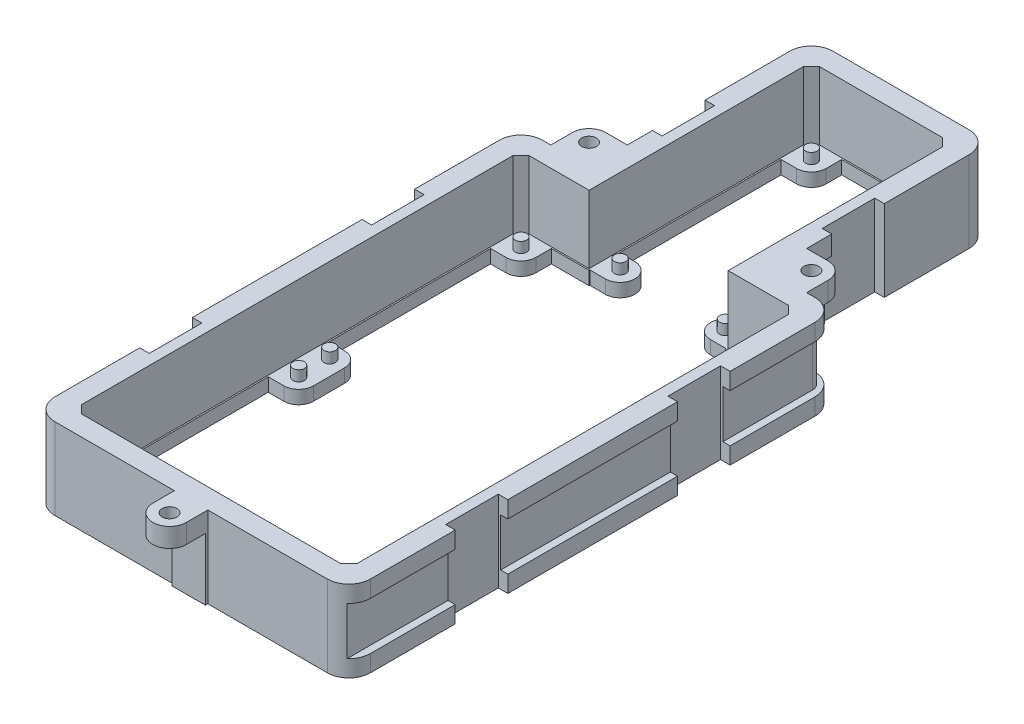
SolidWorks part; units mm, degrees
ref_plane "Front Plane" through (0, 0, 0) normal (0, 0, 1) x (1, 0, 0)
ref_plane "Top Plane" through (0, 0, 0) normal (0, 1, 0) x (1, 0, 0)
ref_plane "Right Plane" through (0, 0, 0) normal (1, 0, 0) x (0, 0, -1)
sketch "Sketch1" plane through (0, 0, 0) normal (0, 1, 0) x (1, 0, 0)
  line L0 (0, 46.5) -> (0, 93) construction
  line L1 (-28.5, 46.5) -> (-14.25, 46.5)
  line L2 (-28.5, 46.5) -> (-28.5, -46.5)
  line L3 (-28.5, -46.5) -> (28.5, -46.5)
  line L4 (28.5, 46.5) -> (28.5, -46.5)
  line L5 (-28.5, 46.5) -> (28.5, -46.5) construction
  line L6 (-28.5, -46.5) -> (28.5, 46.5) construction
  line L7 (14.25, 46.5) -> (28.5, 46.5)
  line L8 (-14.25, 93) -> (14.25, 93)
  line L9 (-14.25, 93) -> (-14.25, 46.5)
  line L11 (14.25, 93) -> (14.25, 46.5)
  line L12 (-14.25, 93) -> (14.25, 46.5) construction
  line L13 (-14.25, 46.5) -> (14.25, 93) construction
  point P0 (0, 0)
  point P8 (0, 69.75)
  dimension "D1" = 93
  dimension "D2" = 57
  dimension "D3" = 28.5
  dimension "D4" = 46.5
extrude "Extrude-Thin1" add sketch "Sketch1" along normal blind 17 thin thin type one direction wall 5
chamfer "Chamfer1" distance 1.5 angle 45 6 edges at (28.5, 8.5, 46.5) (-28.5, 8.5, 46.5) (-14.25, 8.5, -93) (14.25, 8.5, -93) (28.5, 8.5, -46.5) (-28.5, 8.5, -46.5)
sketch "Sketch2" plane through (0, 0, 0) normal (0, 1, 0) x (1, 0, 0)
  line L0 (44.0939, -43.25) -> (-48.3483, -43.25) construction
  line L1 (46.9827, -3.25) -> (-50.6815, -3.25) construction
  line L2 (46.9827, 3.25) -> (-51.7928, 3.25) construction
  line L3 (46.2049, 43.25) -> (-54.3481, 43.25) construction
  line L4 (46.2049, 49.75) -> (-56.7925, 49.75) construction
  line L5 (33.6497, 89.75) -> (-41.3484, 89.75) construction
  line L6 (25.25, -65.6753) -> (25.25, 75.099) construction
  line L7 (-25.25, -68.1197) -> (-25.25, 95.7651) construction
  line L8 (-11, 103.0983) -> (-11, 26.7668) construction
  line L9 (11, 105.5427) -> (11, 26.7668) construction
  line L10 (-27, -46.5) -> (27, -46.5) construction
  line L11 (28.5, -45) -> (28.5, 45) construction
  line L12 (-28.5, 45) -> (-28.5, -45) construction
  line L13 (-14.25, 91.5) -> (-14.25, 46.5) construction
  line L14 (3.25, -77.4697) -> (3.25, -8.4056) construction
  line L15 (14.25, 46.5) -> (14.25, 91.5) construction
  line L16 (27, 46.5) -> (14.25, 46.5) construction
  line L17 (12.75, 93) -> (-12.75, 93) construction
  line L18 (-3.25, -74.7071) -> (-3.25, -10.5676) construction
  circle A0 centre (11, 89.75) radius 1.2
  circle A1 centre (-11, 89.75) radius 1.2
  circle A2 centre (11, 49.75) radius 1.2
  circle A3 centre (-11, 49.75) radius 1.2
  circle A4 centre (25.25, -43.25) radius 1.2
  circle A5 centre (25.25, 43.25) radius 1.2
  circle A6 centre (25.25, 3.25) radius 1.2
  circle A7 centre (25.25, -3.25) radius 1.2
  circle A8 centre (-25.25, -43.25) radius 1.2
  circle A9 centre (-25.25, -3.25) radius 1.2
  circle A10 centre (-25.25, 3.25) radius 1.2
  circle A11 centre (-25.25, 43.25) radius 1.2
  circle A12 centre (3.25, -43.25) radius 1.2
  circle A13 centre (-3.25, -43.25) radius 1.2
  dimension "D11" = 2.4
  dimension "D1" = 3.25
  dimension "D2" = 3.25
  dimension "D3" = 3.25
  dimension "D4" = 40
  dimension "D5" = 6.5
  dimension "D6" = 40
  dimension "D7" = 3.25
  dimension "D8" = 3.25
  dimension "D9" = 3.25
  dimension "D10" = 3.25
  dimension "D12" = 22
  dimension "D13" = 22
extrude "Boss-Extrude1" add sketch "Sketch2" along normal blind 5 separate body
sketch "Sketch3" plane through (0, 0, 0) normal (0, -1, 0) x (-1, 0, 0)
  line L0 (14.25, 53) -> (14.25, 86.5)
  line L1 (7.75, 93) -> (-7.75, 93)
  line L2 (-14.25, 86.5) -> (-14.25, 53)
  line L3 (-14.25, 46.5) -> (-22, 46.5)
  line L4 (-28.5, 40) -> (-28.5, 6.5)
  line L5 (-22, -46.5) -> (-6.5, -46.5)
  line L6 (28.5, -40) -> (28.5, -6.5)
  line L7 (22, 46.5) -> (14.25, 46.5)
  line L8 (22, 43.25) -> (22, 46.5)
  line L9 (25.25, 40) -> (28.5, 40)
  line L10 (25.25, 6.5) -> (28.5, 6.5)
  line L11 (22, 3.25) -> (22, -3.25)
  line L12 (25.25, -6.5) -> (28.5, -6.5)
  line L13 (25.25, -40) -> (28.5, -40)
  line L14 (22, -43.25) -> (22, -46.5)
  line L15 (-25.25, -40) -> (-28.5, -40)
  line L16 (-22, -43.25) -> (-22, -46.5)
  line L17 (-25.25, -6.5) -> (-28.5, -6.5)
  line L18 (-22, -3.25) -> (-22, 3.25)
  line L19 (-25.25, 6.5) -> (-28.5, 6.5)
  line L20 (-25.25, 40) -> (-28.5, 40)
  line L21 (-22, 43.25) -> (-22, 46.5)
  line L22 (-11, 53) -> (-14.25, 53)
  line L23 (-14.25, 46.5) -> (-11, 46.5)
  line L24 (14.25, 46.5) -> (11, 46.5)
  line L25 (11, 53) -> (14.25, 53)
  line L26 (7.75, 89.75) -> (7.75, 93)
  line L27 (11, 86.5) -> (14.25, 86.5)
  line L28 (-11, 86.5) -> (-14.25, 86.5)
  line L29 (-7.75, 89.75) -> (-7.75, 93)
  line L30 (-28.5, -6.5) -> (-28.5, -40)
  line L31 (28.5, 6.5) -> (28.5, 40)
  line L32 (33.5, -51.5) -> (-33.5, -51.5)
  line L33 (-33.5, -51.5) -> (-33.5, 51.5)
  line L34 (-33.5, 51.5) -> (-19.25, 51.5)
  line L35 (-19.25, 51.5) -> (-19.25, 98)
  line L36 (-19.25, 98) -> (19.25, 98)
  line L37 (19.25, 98) -> (19.25, 51.5)
  line L38 (19.25, 51.5) -> (33.5, 51.5)
  line L39 (33.5, 51.5) -> (33.5, -51.5)
  line L40 (-6.5, -43.25) -> (-6.5, -46.5)
  line L41 (-3.25, -40) -> (3.25, -40)
  line L42 (6.5, -43.25) -> (6.5, -46.5)
  line L43 (6.5, -46.5) -> (22, -46.5)
  arc A0 (-11, 46.5) -> (-11, 53) centre (-11, 49.75) ccw
  arc A1 (-11, 86.5) -> (-7.75, 89.75) centre (-11, 89.75) ccw
  arc A2 (7.75, 89.75) -> (11, 86.5) centre (11, 89.75) ccw
  arc A3 (11, 53) -> (11, 46.5) centre (11, 49.75) ccw
  arc A4 (22, 43.25) -> (25.25, 40) centre (25.25, 43.25) ccw
  arc A5 (25.25, 6.5) -> (22, 3.25) centre (25.25, 3.25) ccw
  arc A6 (22, -3.25) -> (25.25, -6.5) centre (25.25, -3.25) ccw
  arc A7 (25.25, -40) -> (22, -43.25) centre (25.25, -43.25) ccw
  arc A8 (-22, -43.25) -> (-25.25, -40) centre (-25.25, -43.25) ccw
  arc A9 (-25.25, -6.5) -> (-22, -3.25) centre (-25.25, -3.25) ccw
  arc A10 (-22, 3.25) -> (-25.25, 6.5) centre (-25.25, 3.25) ccw
  arc A11 (-25.25, 40) -> (-22, 43.25) centre (-25.25, 43.25) ccw
  arc A13 (6.5, -43.25) -> (3.25, -40) centre (3.25, -43.25) ccw
  arc A14 (-3.25, -40) -> (-6.5, -43.25) centre (-3.25, -43.25) ccw
extrude "Boss-Extrude3" add sketch "Sketch3" against normal blind 2.8
sketch "Sketch4" plane through (0, 17, 0) normal (0, 1, 0) x (1, 0, 0)
  line L0 (-19.25, 98) -> (-19.25, 51.5) construction
  line L1 (-19.25, 51.5) -> (-33.5, 51.5) construction
  line L2 (-27.25, 55.5) -> (-27.25, 51.5)
  line L3 (-27.25, 51.5) -> (-19.25, 51.5)
  line L4 (-19.25, 51.5) -> (-19.25, 59.5)
  line L5 (-19.25, 59.5) -> (-23.25, 59.5)
  line L6 (19.25, 51.5) -> (19.25, 98) construction
  line L7 (33.5, 51.5) -> (19.25, 51.5) construction
  line L8 (23.25, 59.5) -> (19.25, 59.5)
  line L9 (19.25, 59.5) -> (19.25, 51.5)
  line L10 (19.25, 51.5) -> (27.25, 51.5)
  line L11 (27.25, 51.5) -> (27.25, 55.5)
  arc A0 (-23.25, 59.5) -> (-27.25, 55.5) centre (-23.25, 55.5) ccw
  circle A1 centre (-23.25, 55.5) radius 1.55
  arc A2 (27.25, 55.5) -> (23.25, 59.5) centre (23.25, 55.5) ccw
  circle A3 centre (23.25, 55.5) radius 1.55
  dimension "D1" = 8
  dimension "D2" = 8
extrude "Boss-Extrude4" add sketch "Sketch4" against normal blind 4
sketch "Sketch5" plane through (0, 17, 0) normal (0, 1, 0) x (1, 0, 0)
  line L0 (-33.5, -51.5) -> (33.5, -51.5) construction
  line L1 (-4, -55.5) -> (-4, -51.5)
  line L2 (-4, -51.5) -> (4, -51.5)
  line L3 (4, -51.5) -> (4, -55.5)
  arc A0 (-4, -55.5) -> (4, -55.5) centre (0, -55.5) ccw
  circle A1 centre (0, -55.5) radius 1.55
  dimension "D1" = 8
  dimension "D2" = 4
extrude "Boss-Extrude5" add sketch "Sketch5" against normal blind 4
fillet "Fillet1" radius 5 6 edges at (-19.25, 8.5, -98) (-33.5, 8.5, -51.5) (-33.5, 8.5, 51.5) (33.5, 8.5, 51.5) (19.25, 8.5, -98) (33.5, 8.5, -51.5)
sketch "Sketch6" plane through (0, 17, 0) normal (0, 1, 0) x (1, 0, 0)
  line L0 (-25.25, 6.5) -> (-25.25, 40) construction
  line L1 (25.25, 40) -> (25.25, 6.5) construction
  line L2 (-25.25, -6.5) -> (-25.25, -40) construction
  line L3 (25.25, -6.5) -> (25.25, -40) construction
  line L4 (0, -23.25) -> (-33.5, -23.25) construction
  line L5 (-33.5, 46.5) -> (-33.5, -46.5) construction
  line L6 (0, -23.25) -> (33.5, -23.25) construction
  line L7 (33.5, -46.5) -> (33.5, 46.5) construction
  line L8 (0, 23.25) -> (-33.5, 23.25) construction
  line L9 (0, 23.25) -> (33.5, 23.25) construction
  line L10 (-11, 53) -> (-11, 86.5) construction
  line L11 (31.5, -28.25) -> (35.5, -28.25)
  line L12 (31.5, -28.25) -> (31.5, -18.25)
  line L13 (31.5, -18.25) -> (35.5, -18.25)
  line L14 (35.5, -28.25) -> (35.5, -18.25)
  line L15 (31.5, -28.25) -> (35.5, -18.25) construction
  line L16 (31.5, -18.25) -> (35.5, -28.25) construction
  line L17 (31.5, 18.25) -> (35.5, 18.25)
  line L18 (31.5, 18.25) -> (31.5, 28.25)
  line L19 (31.5, 28.25) -> (35.5, 28.25)
  line L20 (35.5, 18.25) -> (35.5, 28.25)
  line L21 (31.5, 18.25) -> (35.5, 28.25) construction
  line L22 (31.5, 28.25) -> (35.5, 18.25) construction
  line L23 (-31.5, 18.25) -> (-35.5, 18.25)
  line L24 (-31.5, 18.25) -> (-31.5, 28.25)
  line L25 (-31.5, 28.25) -> (-35.5, 28.25)
  line L26 (-35.5, 18.25) -> (-35.5, 28.25)
  line L27 (-31.5, 18.25) -> (-35.5, 28.25) construction
  line L28 (-31.5, 28.25) -> (-35.5, 18.25) construction
  line L29 (-31.5, -28.25) -> (-35.5, -28.25)
  line L30 (-31.5, -28.25) -> (-31.5, -18.25)
  line L31 (-31.5, -18.25) -> (-35.5, -18.25)
  line L32 (-35.5, -28.25) -> (-35.5, -18.25)
  line L33 (-31.5, -28.25) -> (-35.5, -18.25) construction
  line L34 (-31.5, -18.25) -> (-35.5, -28.25) construction
  line L35 (11, 86.5) -> (11, 53) construction
  line L36 (14.25, 53) -> (11, 53) construction
  line L37 (0, 69.75) -> (-19.25, 69.75) construction
  line L38 (-19.25, 93) -> (-19.25, 59.5) construction
  line L39 (0, 69.75) -> (19.25, 69.75) construction
  line L40 (19.25, 59.5) -> (19.25, 93) construction
  line L42 (-21.25, 64.75) -> (-17.25, 64.75)
  line L43 (-21.25, 64.75) -> (-21.25, 74.75)
  line L44 (-21.25, 74.75) -> (-17.25, 74.75)
  line L45 (-17.25, 64.75) -> (-17.25, 74.75)
  line L46 (-21.25, 64.75) -> (-17.25, 74.75) construction
  line L47 (-21.25, 74.75) -> (-17.25, 64.75) construction
  line L48 (17.25, 64.75) -> (21.25, 64.75)
  line L49 (17.25, 64.75) -> (17.25, 74.75)
  line L50 (17.25, 74.75) -> (21.25, 74.75)
  line L51 (21.25, 64.75) -> (21.25, 74.75)
  line L52 (17.25, 64.75) -> (21.25, 74.75) construction
  line L53 (17.25, 74.75) -> (21.25, 64.75) construction
  arc A0 (-25.25, 40) -> (-22, 43.25) centre (-25.25, 43.25) ccw construction
  arc A1 (11, 53) -> (11, 46.5) centre (11, 49.75) ccw construction
  dimension "D1" = 10
  dimension "D2" = 4
  dimension "D3" = 10
  dimension "D4" = 4
  dimension "D5" = 4
  dimension "D6" = 10
  dimension "D7" = 10
  dimension "D8" = 4
  dimension "D9" = 10
  dimension "D10" = 4
  dimension "D11" = 10
  dimension "D12" = 4
extrude "Cut-Extrude1" cut sketch "Sketch6" against normal through all
sketch "Sketch7" plane through (-33.5, 0, 0) normal (-1, 0, 0) x (0, 0, 1)
  line L0 (51.5, 8.5) -> (-51.5, 8.5)
  line L1 (51.5, 17) -> (51.5, 0) construction
  line L2 (-51.5, 0) -> (-51.5, 17) construction
extrude "Cut-Extrude-Thin1" cut sketch "Sketch7" against normal blind 2 and the other way through all thin thin type mid plane wall 10
sketch "Sketch8" plane through (33.5, 0, 0) normal (1, 0, 0) x (0, 0, -1)
  line L0 (-51.5, 8.5) -> (51.5, 8.5)
  line L1 (-51.5, 0) -> (-51.5, 17) construction
  line L2 (51.5, 13) -> (51.5, 0) construction
extrude "Cut-Extrude-Thin2" cut sketch "Sketch8" against normal blind 2 and the other way through all thin thin type mid plane wall 10
sketch "Sketch9" plane through (19.25, 0, 0) normal (1, 0, 0) x (0, 0, -1)
  line L1 (64.75, 0) -> (51.5, 0)
  line L2 (64.75, 0) -> (64.75, 13)
  line L3 (64.75, 13) -> (51.5, 13)
  line L4 (51.5, 0) -> (51.5, 13)
extrude "Cut-Extrude2" cut sketch "Sketch9" against normal blind 2
sketch "Sketch10" plane through (31.5, 0, 0) normal (1, 0, 0) x (0, 0, -1)
  line L0 (50.5, 3.5) -> (51.5, 3.5)
  line L1 (51.5, 13) -> (51.5, 0) construction
  line L2 (51.5, 3.5) -> (51.5, 13)
  line L3 (64.75, 13) -> (51.5, 13) construction
  line L4 (51.5, 13) -> (49.5, 13)
  line L5 (49.5, 13) -> (49.5, 3.5)
  line L6 (28.25, 3.5) -> (50.5, 3.5) construction
  line L7 (49.5, 3.5) -> (50.5, 3.5)
  dimension "D1" = 2
extrude "Cut-Extrude3" cut sketch "Sketch10" against normal up to surface (14.25 mm away) up to face at (17.25, 10, -63.6667)
fillet "Fillet2" radius 2 1 edges at (31.5, 8.25, -49.5)
sketch "Sketch11" plane through (-19.25, 0, 0) normal (-1, 0, 0) x (0, 0, 1)
  line L1 (-64.75, 0) -> (-51.5, 0)
  line L2 (-64.75, 0) -> (-64.75, 13)
  line L3 (-64.75, 13) -> (-51.5, 13)
  line L4 (-51.5, 0) -> (-51.5, 13)
extrude "Cut-Extrude4" cut sketch "Sketch11" against normal blind 2
sketch "Sketch12" plane through (-31.5, 0, 0) normal (-1, 0, 0) x (0, 0, 1)
  line L0 (-46.5, 3.5) -> (-50.5, 3.5) construction
  line L1 (-51.5, 13) -> (-49.5, 13)
  line L2 (-51.5, 13) -> (-51.5, 3.5)
  line L3 (-51.5, 3.5) -> (-49.5, 3.5)
  line L4 (-49.5, 13) -> (-49.5, 3.5)
  dimension "D1" = 2
extrude "Cut-Extrude5" cut sketch "Sketch12" against normal up to surface (14.25 mm away) up to face at (-17.25, 10, -63.6667)
fillet "Fillet3" radius 2 1 edges at (-31.5, 8.25, -49.5)
sketch "Sketch13" plane through (0, 17, 0) normal (0, 1, 0) x (1, 0, 0)
  line L39 (-17.25, 64.75) -> (-19.25, 64.75)
  line L40 (-19.25, 64.75) -> (-19.25, 59.5)
  line L41 (-19.25, 59.5) -> (-23.25, 59.5)
  line L42 (-27.25, 55.5) -> (-27.25, 51.5)
  line L43 (-27.25, 51.5) -> (-28.5, 51.5)
  line L44 (-33.5, 46.5) -> (-33.5, 28.25)
  line L45 (-33.5, 28.25) -> (-31.5, 28.25)
  line L46 (-31.5, 28.25) -> (-31.5, 18.25)
  line L47 (-31.5, 18.25) -> (-33.5, 18.25)
  line L48 (-33.5, 18.25) -> (-33.5, -18.25)
  line L49 (-33.5, -18.25) -> (-31.5, -18.25)
  line L50 (-31.5, -18.25) -> (-31.5, -28.25)
  line L51 (-31.5, -28.25) -> (-33.5, -28.25)
  line L52 (-33.5, -28.25) -> (-33.5, -46.5)
  line L53 (-28.5, -51.5) -> (-4, -51.5)
  line L54 (-4, -51.5) -> (-4, -55.5)
  line L55 (4, -55.5) -> (4, -51.5)
  line L56 (4, -51.5) -> (28.5, -51.5)
  line L57 (33.5, -46.5) -> (33.5, -28.25)
  line L58 (33.5, -28.25) -> (31.5, -28.25)
  line L59 (31.5, -28.25) -> (31.5, -18.25)
  line L60 (31.5, -18.25) -> (33.5, -18.25)
  line L61 (33.5, -18.25) -> (33.5, 18.25)
  line L62 (33.5, 18.25) -> (31.5, 18.25)
  line L63 (31.5, 18.25) -> (31.5, 28.25)
  line L64 (31.5, 28.25) -> (33.5, 28.25)
  line L65 (33.5, 28.25) -> (33.5, 46.5)
  line L66 (28.5, 51.5) -> (27.25, 51.5)
  line L67 (27.25, 51.5) -> (27.25, 55.5)
  line L68 (23.25, 59.5) -> (19.25, 59.5)
  line L69 (19.25, 59.5) -> (19.25, 64.75)
  line L70 (19.25, 64.75) -> (17.25, 64.75)
  line L71 (17.25, 64.75) -> (17.25, 74.75)
  line L72 (17.25, 74.75) -> (19.25, 74.75)
  line L73 (19.25, 74.75) -> (19.25, 93)
  line L74 (14.25, 98) -> (-14.25, 98)
  line L75 (-19.25, 93) -> (-19.25, 74.75)
  line L76 (-19.25, 74.75) -> (-17.25, 74.75)
  line L77 (-17.25, 74.75) -> (-17.25, 64.75)
  line L78 (-17.25, 64.75) -> (-19.25, 64.75)
  line L79 (-19.25, 64.75) -> (-19.25, 59.5)
  line L80 (-19.25, 59.5) -> (-23.25, 59.5)
  line L81 (-27.25, 55.5) -> (-27.25, 51.5)
  line L82 (-27.25, 51.5) -> (-28.5, 51.5)
  line L83 (-33.5, 46.5) -> (-33.5, 28.25)
  line L84 (-33.5, 28.25) -> (-31.5, 28.25)
  line L85 (-31.5, 28.25) -> (-31.5, 18.25)
  line L86 (-31.5, 18.25) -> (-33.5, 18.25)
  line L87 (-33.5, 18.25) -> (-33.5, -18.25)
  line L88 (-33.5, -18.25) -> (-31.5, -18.25)
  line L89 (-31.5, -18.25) -> (-31.5, -28.25)
  line L90 (-31.5, -28.25) -> (-33.5, -28.25)
  line L91 (-33.5, -28.25) -> (-33.5, -46.5)
  line L92 (-28.5, -51.5) -> (-4, -51.5)
  line L93 (-4, -51.5) -> (-4, -55.5)
  line L94 (4, -55.5) -> (4, -51.5)
  line L95 (4, -51.5) -> (28.5, -51.5)
  line L96 (33.5, -46.5) -> (33.5, -28.25)
  line L97 (33.5, -28.25) -> (31.5, -28.25)
  line L98 (31.5, -28.25) -> (31.5, -18.25)
  line L99 (31.5, -18.25) -> (33.5, -18.25)
  line L100 (33.5, -18.25) -> (33.5, 18.25)
  line L101 (33.5, 18.25) -> (31.5, 18.25)
  line L102 (31.5, 18.25) -> (31.5, 28.25)
  line L103 (31.5, 28.25) -> (33.5, 28.25)
  line L104 (33.5, 28.25) -> (33.5, 46.5)
  line L105 (28.5, 51.5) -> (27.25, 51.5)
  line L106 (27.25, 51.5) -> (27.25, 55.5)
  line L107 (23.25, 59.5) -> (19.25, 59.5)
  line L108 (19.25, 59.5) -> (19.25, 64.75)
  line L109 (19.25, 64.75) -> (17.25, 64.75)
  line L110 (17.25, 64.75) -> (17.25, 74.75)
  line L111 (17.25, 74.75) -> (19.25, 74.75)
  line L112 (19.25, 74.75) -> (19.25, 93)
  line L113 (14.25, 98) -> (-14.25, 98)
  line L114 (-19.25, 93) -> (-19.25, 74.75)
  line L115 (-19.25, 74.75) -> (-17.25, 74.75)
  line L116 (-17.25, 74.75) -> (-17.25, 64.75)
  arc A9 (-23.25, 59.5) -> (-27.25, 55.5) centre (-23.25, 55.5) ccw
  arc A10 (-28.5, 51.5) -> (-33.5, 46.5) centre (-28.5, 46.5) ccw
  arc A11 (-33.5, -46.5) -> (-28.5, -51.5) centre (-28.5, -46.5) ccw
  arc A12 (-4, -55.5) -> (4, -55.5) centre (0, -55.5) ccw
  arc A13 (28.5, -51.5) -> (33.5, -46.5) centre (28.5, -46.5) ccw
  arc A14 (33.5, 46.5) -> (28.5, 51.5) centre (28.5, 46.5) ccw
  arc A15 (27.25, 55.5) -> (23.25, 59.5) centre (23.25, 55.5) ccw
  arc A16 (19.25, 93) -> (14.25, 98) centre (14.25, 93) ccw
  arc A17 (-14.25, 98) -> (-19.25, 93) centre (-14.25, 93) ccw
  arc A18 (-23.25, 59.5) -> (-27.25, 55.5) centre (-23.25, 55.5) ccw
  arc A19 (-28.5, 51.5) -> (-33.5, 46.5) centre (-28.5, 46.5) ccw
  arc A20 (-33.5, -46.5) -> (-28.5, -51.5) centre (-28.5, -46.5) ccw
  arc A21 (-4, -55.5) -> (4, -55.5) centre (0, -55.5) ccw
  arc A22 (28.5, -51.5) -> (33.5, -46.5) centre (28.5, -46.5) ccw
  arc A23 (33.5, 46.5) -> (28.5, 51.5) centre (28.5, 46.5) ccw
  arc A24 (27.25, 55.5) -> (23.25, 59.5) centre (23.25, 55.5) ccw
  arc A25 (19.25, 93) -> (14.25, 98) centre (14.25, 93) ccw
  arc A26 (-14.25, 98) -> (-19.25, 93) centre (-14.25, 93) ccw
  dimension "D1" = 0
extrude "Cut-Extrude-Thin4" cut sketch "Sketch13" against normal blind 20 thin contours L78 L79 L80 A18 L81 L82 A19 L83 L84 L85 L86 L87 L88 L89 L90 L91 A20 L92 L93 A21 L94 L95 A22 L96 L97 L98 L99 L100 L101 L102 L103 L104 A23 L105 L106 A24 L107 L108 L109 L110 L111 L112 A25 L113 A26 L114 L115 L116 thin type one direction reverse wall 0.5
sketch "Sketch14" plane through (0, 2.8, 0) normal (0, 1, 0) x (1, 0, 0)
  line L0 (7.75, 93) -> (7.75, 89.75)
  line L1 (11, 86.5) -> (14.25, 86.5)
  line L2 (-7.75, 93) -> (-7.75, 89.75)
  line L3 (-11, 86.5) -> (-14.25, 86.5)
  line L4 (-14.25, 53) -> (-11, 53)
  line L5 (-11, 46.5) -> (-14.25, 46.5)
  line L6 (14.25, 53) -> (11, 53)
  line L7 (11, 46.5) -> (14.25, 46.5)
  line L8 (22, 46.5) -> (22, 43.25)
  line L9 (25.25, 40) -> (28.5, 40)
  line L10 (28.5, 6.5) -> (25.25, 6.5)
  line L11 (22, 3.25) -> (22, -3.25)
  line L12 (25.25, -6.5) -> (28.5, -6.5)
  line L13 (28.5, -40) -> (25.25, -40)
  line L14 (22, -43.25) -> (22, -46.5)
  line L15 (6.5, -46.5) -> (6.5, -43.25)
  line L16 (3.25, -40) -> (-3.25, -40)
  line L17 (-6.5, -43.25) -> (-6.5, -46.5)
  line L18 (-22, -46.5) -> (-22, -43.25)
  line L19 (-25.25, -40) -> (-28.5, -40)
  line L20 (-28.5, -6.5) -> (-25.25, -6.5)
  line L21 (-22, -3.25) -> (-22, 3.25)
  line L22 (-25.25, 6.5) -> (-28.5, 6.5)
  line L23 (-28.5, 40) -> (-25.25, 40)
  line L24 (-22, 43.25) -> (-22, 46.5)
  arc A0 (7.75, 89.75) -> (11, 86.5) centre (11, 89.75) ccw
  arc A1 (-7.75, 89.75) -> (-11, 86.5) centre (-11, 89.75) cw
  arc A2 (-11, 53) -> (-11, 46.5) centre (-11, 49.75) cw
  arc A3 (11, 53) -> (11, 46.5) centre (11, 49.75) ccw
  arc A4 (22, 43.25) -> (25.25, 40) centre (25.25, 43.25) ccw
  arc A5 (25.25, 6.5) -> (22, 3.25) centre (25.25, 3.25) ccw
  arc A6 (22, -3.25) -> (25.25, -6.5) centre (25.25, -3.25) ccw
  arc A7 (25.25, -40) -> (22, -43.25) centre (25.25, -43.25) ccw
  arc A8 (6.5, -43.25) -> (3.25, -40) centre (3.25, -43.25) ccw
  arc A9 (-3.25, -40) -> (-6.5, -43.25) centre (-3.25, -43.25) ccw
  arc A10 (-22, -43.25) -> (-25.25, -40) centre (-25.25, -43.25) ccw
  arc A11 (-25.25, -6.5) -> (-22, -3.25) centre (-25.25, -3.25) ccw
  arc A12 (-22, 3.25) -> (-25.25, 6.5) centre (-25.25, 3.25) ccw
  arc A13 (-22, 3.25) -> (-25.25, 6.5) centre (-25.25, 3.25) ccw construction
  arc A14 (-25.25, 40) -> (-22, 43.25) centre (-25.25, 43.25) ccw
extrude "Cut-Extrude-Thin5" cut sketch "Sketch14" against normal blind 10 thin thin type mid plane wall 0.3
sketch "Sketch15" plane through (0, 17, 0) normal (0, 1, 0) x (1, 0, 0)
  line L0 (14.25, 46.5) -> (14.25, 91.5)
  line L1 (14.25, 91.5) -> (12.75, 93)
  line L2 (12.75, 93) -> (-12.75, 93)
  line L3 (-12.75, 93) -> (-14.25, 91.5)
  line L4 (-14.25, 91.5) -> (-14.25, 46.5)
  line L5 (-14.25, 46.5) -> (-27, 46.5)
  line L6 (-27, 46.5) -> (-28.5, 45)
  line L7 (-28.5, 45) -> (-28.5, -45)
  line L8 (-28.5, -45) -> (-27, -46.5)
  line L9 (-27, -46.5) -> (27, -46.5)
  line L10 (27, -46.5) -> (28.5, -45)
  line L11 (28.5, -45) -> (28.5, 45)
  line L12 (28.5, 45) -> (27, 46.5)
  line L13 (27, 46.5) -> (14.25, 46.5)
extrude "Cut-Extrude-Thin6" cut sketch "Sketch15" against normal up to surface (14.2 mm away) thin
